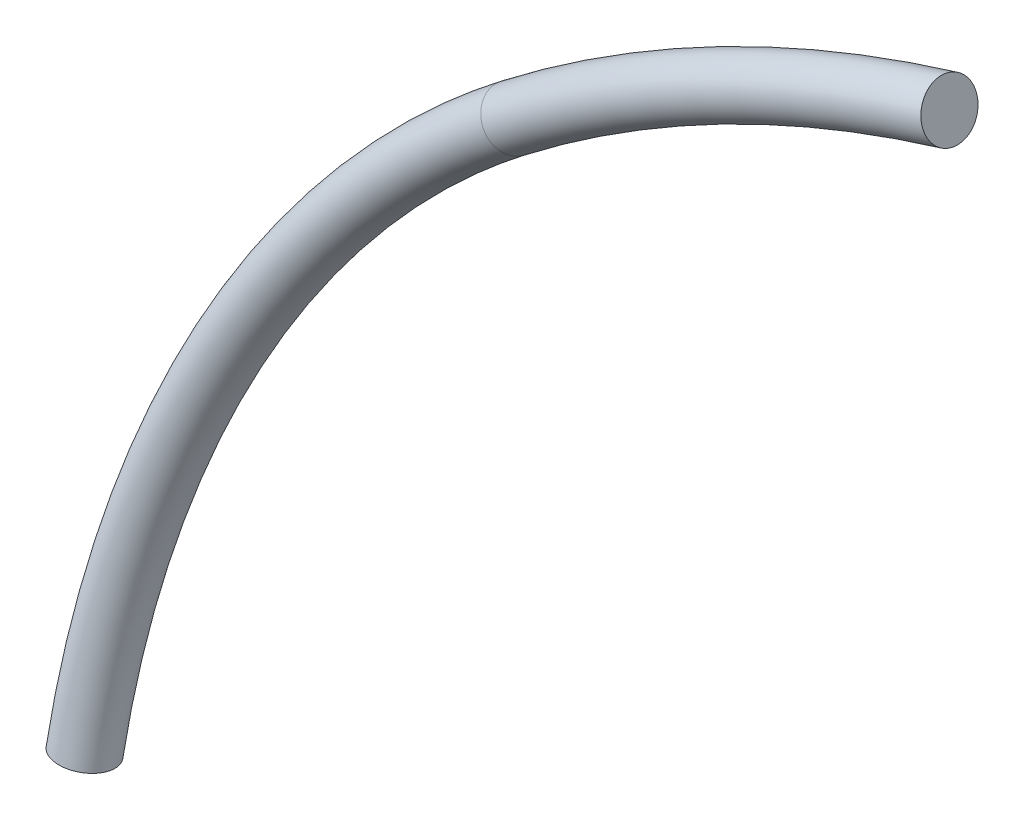
SolidWorks part; units mm, degrees
ref_plane "Front" through (0, 0, 0) normal (0, 0, 1) x (1, 0, 0)
ref_plane "Top" through (0, 0, 0) normal (0, 1, 0) x (1, 0, 0)
ref_plane "Right" through (0, 0, 0) normal (1, 0, 0) x (0, 0, -1)
sketch "Sketch1" plane through (0, 0, 0) normal (0, 0, 1) x (1, 0, 0)
  line L0 (1312.5285, -486.9994) -> (456.0636, -1147.9203) construction
  arc A0 (2120.7701, -70.1343) -> (1312.5285, -486.9994) centre (2855.2641, -2486.178) ccw
  arc A1 (3300.9211, -195.5094) -> (2120.7701, -70.1343) centre (2562.9751, -1524.7227) ccw construction
  spline S0 degree 3 poles (12.6287, -1542.4185) (1660.0512, -1247.4612) (1396.184, -2572.0697) (2552.1536, -3378.376) (3653.2248, -3381.0744) (4498.8593, -2410.0471) (4234.3259, -1332.1122) (3828.4317, -438.5455) (2878.5173, 34.0308) (1828.4268, -38.3903) (848.7491, -832.9542) (478.3486, -2168.9227) (655.66, -3702.3879) (1776.0331, -4731.1943) (3233.2155, -4916.8204) (4680.4296, -4726.8399) (6307.3282, -3696.4175) (7469.1656, -2286.7006) (7106.2538, 15.9001) (6390.1027, 1605.915) (4943.9608, 2829.7833) (3528.655, 3564.3804) (2398.2908, 3971.4721) (81.6978, 4346.5877) (-2107.3471, 3741.776) (-3307.6994, 3064.2218) (-4872.4252, 2142.1063) (-6051.5753, 670.5262) (-6903.7379, -1042.8518) (-6660.4419, -2913.7021) (-4530.0051, -4010.9344) (-3278.8488, -4392.9339) (-2255.8989, -4955.8268) knots -0.03564 -0.03564 -0.03564 -0.03564 0.012418 0.026176 0.053223 0.077498 0.099256 0.122387 0.140197 0.165808 0.187601 0.21914 0.254189 0.284814 0.311917 0.350124 0.381709 0.440659 0.47622 0.524804 0.564919 0.59506 0.63529 0.679111 0.741875 0.781701 0.810098 0.866605 0.901783 0.935896 0.978749 1.043408 1.043408 1.043408 1.043408 only from (1640.1048, -2343.3491) to (-4072.3026, -4122.4591) construction
  dimension "D1" = 914.4
ref_plane "Plane2" through (22.6161, -29.3074, -206.365) normal (-0.1079, 0.1398, 0.9843) x (0.9942, 0.0144, 0.1069)
sketch "Sketch3" plane through (22.6161, -29.3074, -206.365) normal (-0.1079, 0.1398, 0.9843) x (0.9942, 0.0144, 0.1069)
  line L0 (611.987, -1788.0247) -> (556.2606, -2993.6527) construction
  line L1 (1297.862, -481.1411) -> (436.885, -1136.1732) construction
  arc A0 (1297.862, -481.1411) -> (611.987, -1788.0247) centre (2353.3773, -1868.515) ccw
  dimension "D1" = 1524
sketch "Sketch4" plane through (1921.8326, 584.2504, 0) normal (-0.9568, -0.2909, 0) x (0, 0, 1)
  circle A0 centre (0, -683.9558) radius 50.8
sweep "Sweep1" add profiles "Sketch4" path "Sketch1"
sketch "Sketch5" plane through (587.1012, 453.0571, 0) normal (-0.7917, -0.6109, 0) x (0, 0, 1)
  line L0 (0, -1187.4135) -> (307.8018, -2903.274) construction
  line L1 (0, -1187.4135) -> (0, -3712.6359) construction
  circle A0 centre (0, -1187.4135) radius 50.8
  dimension "D1" = 10.17
sweep "Sweep2" add profiles "Sketch5" path "Sketch3"
